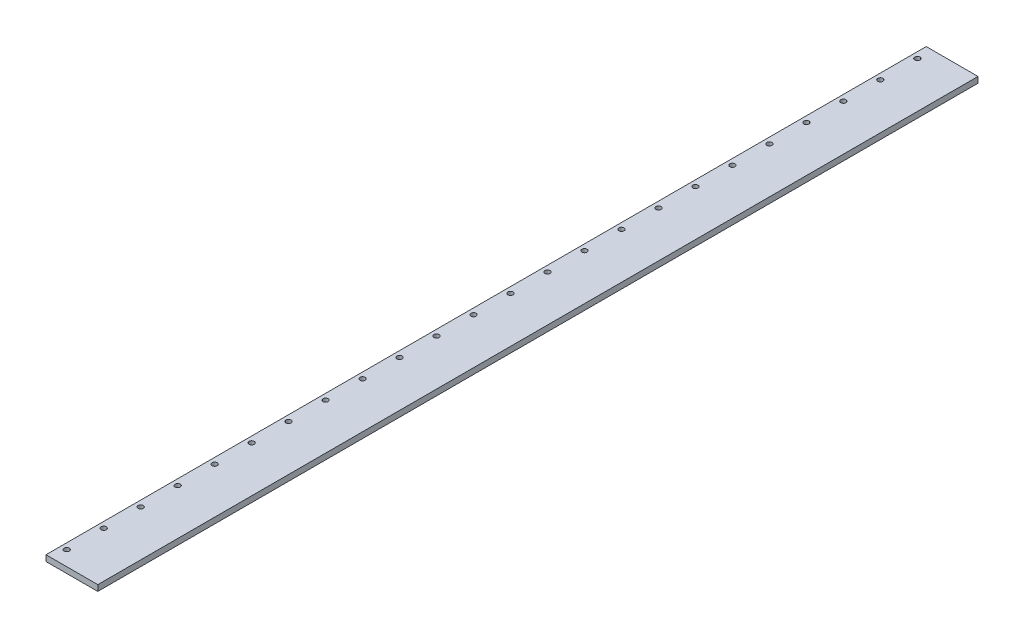
SolidWorks part; units mm, degrees
ref_plane "Front Plane" through (0, 0, 0) normal (0, 0, 1) x (1, 0, 0)
ref_plane "Top Plane" through (0, 0, 0) normal (0, 1, 0) x (1, 0, 0)
ref_plane "Right Plane" through (0, 0, 0) normal (1, 0, 0) x (0, 0, -1)
sketch "Sketch1" plane through (0, 0, 0) normal (0, 0, 1) x (1, 0, 0)
  line L0 (17.5, 2) -> (-17.5, 2)
  line L1 (-17.5, -2) -> (17.5, -2)
  line L4 (17.5, -2) -> (17.5, 2)
  line L5 (-17.5, -2) -> (17.5, 2) construction
  line L9 (-17.5, -2) -> (-17.5, 2)
  point P0 (0, 0)
  point P3 (-17.6198, 2)
  dimension "D1" = 4
extrude "Boss-Extrude2" add sketch "Sketch1" along normal blind 595
sketch "Sketch2" plane through (0, 2, 0) normal (0, 1, 0) x (1, 0, 0)
  line L2 (17.5, 0) -> (-17.5, 0) construction
  line L3 (-17.5, -595) -> (-17.5, 0) construction
  circle A0 centre (-13.5, -10) radius 1.75
  point P4 (0, 0)
  dimension "D1" = 3.5
  dimension "D2" = 10
  dimension "D3" = 4
extrude "Cut-Extrude1" cut sketch "Sketch2" against normal through all
pattern_linear "LPattern1" count 24 spacing 25 along (0, 0, 1) of "Cut-Extrude1"
